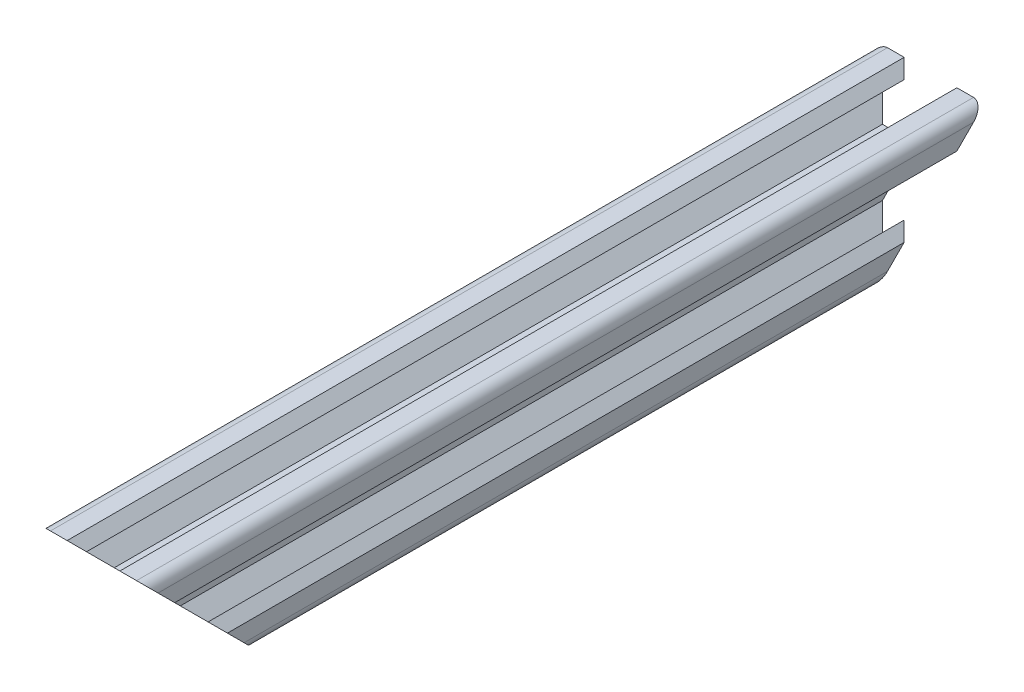
SolidWorks part; units mm, degrees
material "6061 Alloy"
ref_plane "Front Plane" through (0, 0, 0) normal (0, 0, 1) x (1, 0, 0)
ref_plane "Top Plane" through (0, 0, 0) normal (0, 1, 0) x (1, 0, 0)
ref_plane "Right Plane" through (0, 0, 0) normal (1, 0, 0) x (0, 0, -1)
sketch "Sketch1" plane through (0, 0, 0) normal (0, 0, 1) x (1, 0, 0)
  line L0 (-4.9, -10) -> (-5.5, -10)
  line L1 (-10, -10) -> (10, -10) construction
  line L2 (-10, -10) -> (-10, 10) construction
  line L3 (-10, 10) -> (10, 10) construction
  line L4 (10, -10) -> (10, 10) construction
  line L5 (-10, -10) -> (10, 10) construction
  line L6 (-10, 10) -> (10, -10) construction
  line L7 (-3.6, 3.6) -> (3.6, 3.6)
  line L8 (-3.6, 3.6) -> (-3.6, -3.6)
  line L9 (-3.6, -3.6) -> (3.6, -3.6)
  line L10 (3.6, 3.6) -> (3.6, -3.6)
  line L11 (-8, 10) -> (-5.5, 10)
  line L12 (-10, 8) -> (-10, 5.5)
  line L13 (-10, 5.5) -> (-5.5, 5.5)
  line L14 (-5.5, 10) -> (-5.5, 5.5)
  line L15 (8, 10) -> (5.5, 10)
  line L16 (10, 8) -> (10, 5.5)
  line L17 (10, 5.5) -> (5.5, 5.5)
  line L18 (5.5, 10) -> (5.5, 5.5)
  line L19 (8, -10) -> (5.5, -10)
  line L20 (10, -8) -> (10, -5.5)
  line L21 (10, -5.5) -> (5.5, -5.5)
  line L22 (5.5, -10) -> (5.5, -5.5)
  line L23 (-8, -10) -> (-5.5, -10)
  line L24 (-10, -8) -> (-10, -5.5)
  line L25 (-10, -5.5) -> (-5.5, -5.5)
  line L26 (-5.5, -10) -> (-5.5, -5.5)
  line L27 (-3.1, -8.2) -> (-4.9, -10)
  line L28 (-3.1, -8.2) -> (-5.5, -8.2)
  line L29 (4.9, -10) -> (5.5, -10)
  line L30 (3.1, -8.2) -> (4.9, -10)
  line L31 (3.1, -8.2) -> (5.5, -8.2)
  line L32 (-4.9, 10) -> (-5.5, 10)
  line L33 (-3.1, 8.2) -> (-4.9, 10)
  line L34 (-3.1, 8.2) -> (-5.5, 8.2)
  line L35 (4.9, 10) -> (5.5, 10)
  line L36 (0, 0) -> (17.4618, 0) construction
  line L37 (3.1, 8.2) -> (4.9, 10)
  line L38 (3.1, 8.2) -> (5.5, 8.2)
  line L39 (8.2, 3.1) -> (8.2, 5.5)
  line L40 (8.2, 3.1) -> (10, 4.9)
  line L41 (10, 4.9) -> (10, 5.5)
  line L42 (10, -4.9) -> (10, -5.5)
  line L43 (8.2, -3.1) -> (10, -4.9)
  line L44 (8.2, -3.1) -> (8.2, -5.5)
  line L57 (-8.2, -3.1) -> (-10, -4.9)
  line L58 (-10, -4.9) -> (-10, -5.5)
  line L61 (-8.2, -3.1) -> (-8.2, -5.5)
  line L62 (-8.2, 3.1) -> (-10, 4.9)
  line L63 (-10, 4.9) -> (-10, 5.5)
  line L66 (-8.2, 3.1) -> (-8.2, 5.5)
  line L67 (-2.7729, 2.7729) -> (-6.4508, 6.4508) construction
  line L68 (-2.2426, 3.3033) -> (-5.9205, 6.9812)
  line L69 (-3.3033, 2.2426) -> (-6.9812, 5.9205)
  line L70 (6.7372, 6.7372) -> (2.7729, 2.7729)
  line L71 (6.309, -6.309) -> (2.7729, -2.7729)
  line L72 (-2.8687, -2.8687) -> (-6.5971, -6.5971)
  line L73 (6.2069, 7.2675) -> (2.2426, 3.3033)
  line L74 (6.8393, -5.7786) -> (3.3033, -2.2426)
  line L75 (-3.399, -2.3384) -> (-7.1274, -6.0667)
  line L76 (7.2675, 6.2069) -> (3.3033, 2.2426)
  line L77 (5.7786, -6.8393) -> (2.2426, -3.3033)
  line L78 (-2.3384, -3.399) -> (-6.0667, -7.1274)
  circle A0 centre (0, 0) radius 2.1
  arc A1 (-8, -10) -> (-10, -8) centre (-8, -8) cw
  arc A2 (8, -10) -> (10, -8) centre (8, -8) ccw
  arc A3 (8, 10) -> (10, 8) centre (8, 8) cw
  arc A4 (-8, 10) -> (-10, 8) centre (-8, 8) ccw
  point P0 (0, 0)
  dimension "D3" = 4.2
  dimension "D12" = 2
  dimension "D1" = 20
  dimension "D4" = 6.4
  dimension "D5" = 6.4
  dimension "D6" = 6.4
  dimension "D7" = 6.4
  dimension "D8" = 4.5
  dimension "D9" = 4.5
  dimension "D10" = 4.5
  dimension "D11" = 4.5
  dimension "D13" = 45
  dimension "D19" = 45
  dimension "D20" = 6.2
  dimension "D23" = 1.8
  dimension "D24" = 1.8
  dimension "D28" = 0.75
  dimension "D26" = 0.75
  dimension "D27" = 0.75
  dimension "D29" = 0.75
extrude "Boss-Extrude1" add sketch "Sketch1" along normal blind 155.6
sketch "Sketch2" plane through (-10, 0, 0) normal (-1, 0, 0) x (0, 0, 1)
  line L0 (155.6, 10) -> (135.6, -10)
  line L1 (155.6, -10) -> (0, -10) construction
  line L2 (155.6, 8) -> (155.6, 4.9) construction
  line L3 (77.8, 10) -> (77.8, -10) construction
  line L5 (155.6, 10) -> (0, 10) construction
  line L6 (0, 10) -> (20, -10)
  line L7 (135.6, -10) -> (155.6, -10)
  line L8 (155.6, -10) -> (155.6, 10)
  line L9 (20, -10) -> (0, -10)
  line L11 (0, -10) -> (0, 10)
  dimension "D1" = 45
extrude "Cut-Extrude1" cut sketch "Sketch2" against normal blind 66
